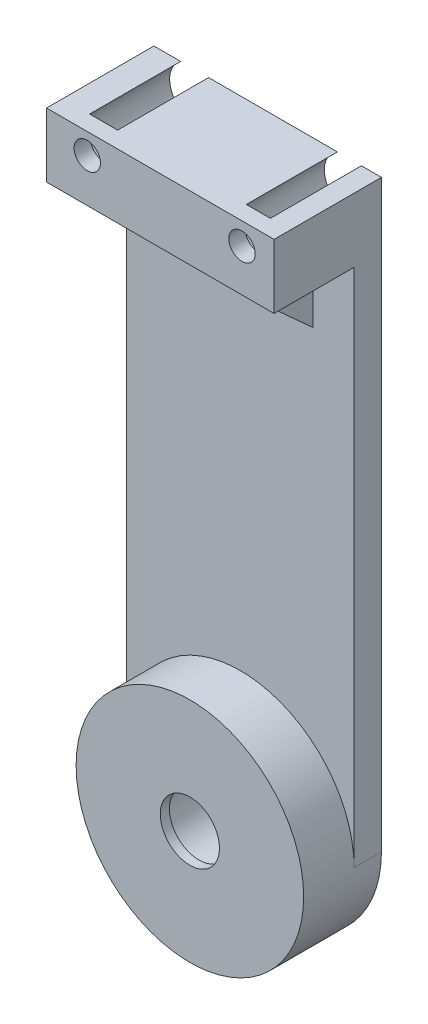
SolidWorks part; units mm, degrees
ref_plane "Plano frontal" through (0, 0, 0) normal (0, 0, 1) x (1, 0, 0)
ref_plane "Plano superior" through (0, 0, 0) normal (0, 1, 0) x (1, 0, 0)
ref_plane "Plano direito" through (0, 0, 0) normal (1, 0, 0) x (0, 0, -1)
sketch "Esboço2" plane through (0, 0, 0) normal (0, 0, 1) x (1, 0, 0)
  circle A0 centre (-0.4749, -0.0634) radius 12.5
  arc A1 (12.0247, -0.1594) -> (-12.9746, 0.0325) centre (-0.4749, -0.0634) ccw construction
extrude "Ressalto-extrusão1" add sketch "Esboço2" against normal offset from surface (5.55 mm away) 2
sketch "Esboço4" plane through (0, 0, -5.55) normal (0, 0, -1) x (-1, 0, 0)
  line L0 (-12.0251, -0.0634) -> (-12.0251, 64.1202)
  line L1 (12.9749, -0.0634) -> (12.9749, 64.1202)
  line L2 (12.9749, 64.1202) -> (-12.0251, 64.1202)
  arc A0 (-12.0251, -0.0634) -> (12.9749, -0.0634) centre (0.4749, -0.0634) ccw
  circle A4 centre (0.4749, -0.0634) radius 12.5 construction
  dimension "D1" = 0.5
extrude "Ressalto-extrusão3" add sketch "Esboço4" along normal blind 3
sketch "Esboço5" plane through (0, 0, -8.55) normal (0, 0, -1) x (-1, 0, 0)
  line L0 (12.9749, -0.0634) -> (12.9749, 64.1202) construction
  line L1 (-12.0251, 64.1202) -> (12.9749, 64.1202)
  line L2 (-12.0251, 64.1202) -> (-12.0251, 57.0691)
  line L3 (-12.0251, 57.0691) -> (12.9749, 57.0691)
  line L5 (12.9749, 57.0691) -> (12.9749, 64.1202)
extrude "Ressalto-extrusão4" add sketch "Esboço5" against normal up to surface (11.8 mm away)
hole_wizard "Rebaixo para SHCS M2.51" positions "Esboço6" profile "Esboço7" counterbore size "M2.5" standard "Ansi Metric" end condition up to next
sketch "Esboço6" plane through (0, 0, -8.55) normal (0, 0, -1) x (-1, 0, 0)
  circle A0 centre (-8.4995, 61.7078) radius 1.35 construction
  circle A1 centre (8.5, 61.8383) radius 1.35 construction
  point P0 (-8.4995, 61.7078)
  point P2 (8.5, 61.8383)
sketch "Esboço7" plane through (8.4995, 61.7078, -8.55) normal (1, 0, 0) x (0, 1, 0)
  line L0 (0, 0) -> (0, 11.8)
  line L1 (0, 11.8) -> (1.45, 11.8)
  line L3 (1.45, 11.8) -> (1.45, 10)
  line L4 (1.45, 10) -> (2.75, 10)
  line L5 (2.75, 10) -> (2.75, 0)
  line L7 (2.75, 0) -> (0, 0)
  line L11 (0, -6.35) -> (0, 107.95) construction
  dimension "Thru Hole Dia." = 2.9
  dimension "Thru Hole Depth" = 11.8
  dimension "C'Bore Dia." = 5.5
  dimension "C'Bore Depth" = 10
sketch "Esboço10" plane through (0, 0, 0) normal (1, 0, 0) x (0, 0, -1)
  line L0 (-3.25, 57.0691) -> (5.55, 49.0691)
  line L1 (5.55, -0.0634) -> (5.55, 57.0691) construction
  line L2 (-3.25, 57.0691) -> (5.55, 57.0691) construction
  dimension "D1" = 8
rib "Nervura1" sketch "Esboço10" sketch "Esboço10" thickness 15 extrusion direction parallel to sketch draft on no parameters "D1"=15
sketch "Esboço11" plane through (0, 0, -5.55) normal (0, 0, 1) x (1, 0, 0)
  line L0 (7.5, 49.0691) -> (-7.5, 49.0691) construction
  line L1 (4.5, 49.0691) -> (-4.5, 49.0691)
  line L2 (4.5, 49.0691) -> (4.5, 57.0691)
  line L3 (4.5, 57.0691) -> (-4.5, 57.0691)
  line L4 (-4.5, 49.0691) -> (-4.5, 57.0691)
  line L5 (7.5, 57.0691) -> (-7.5, 57.0691) construction
  line L6 (7.5, 57.0691) -> (7.5, 49.0691) construction
  point P8 (0, 57.0691)
  point P9 (0, 57.0691)
  dimension "D1" = 3
extrude "Corte-extrusão1" cut sketch "Esboço11" along normal up to next
sketch "Esboço12" plane through (0, 0, -8.55) normal (0, 0, -1) x (-1, 0, 0)
  circle A0 centre (0.4749, -0.0634) radius 3.25 construction
  circle A1 centre (0.4749, -0.0634) radius 3.25
extrude "Corte-extrusão2" cut sketch "Esboço12" against normal through all
sketch "Esboço13" plane through (0, 0, -8.55) normal (0, 0, -1) x (-1, 0, 0)
  circle A0 centre (0.4749, -0.0634) radius 4 construction
  circle A1 centre (0.4749, -0.0634) radius 4
extrude "Corte-extrusão3" cut sketch "Esboço13" against normal offset from surface (7.55 mm away) 1 up to face at (2.7751, -0.0634, 0)
